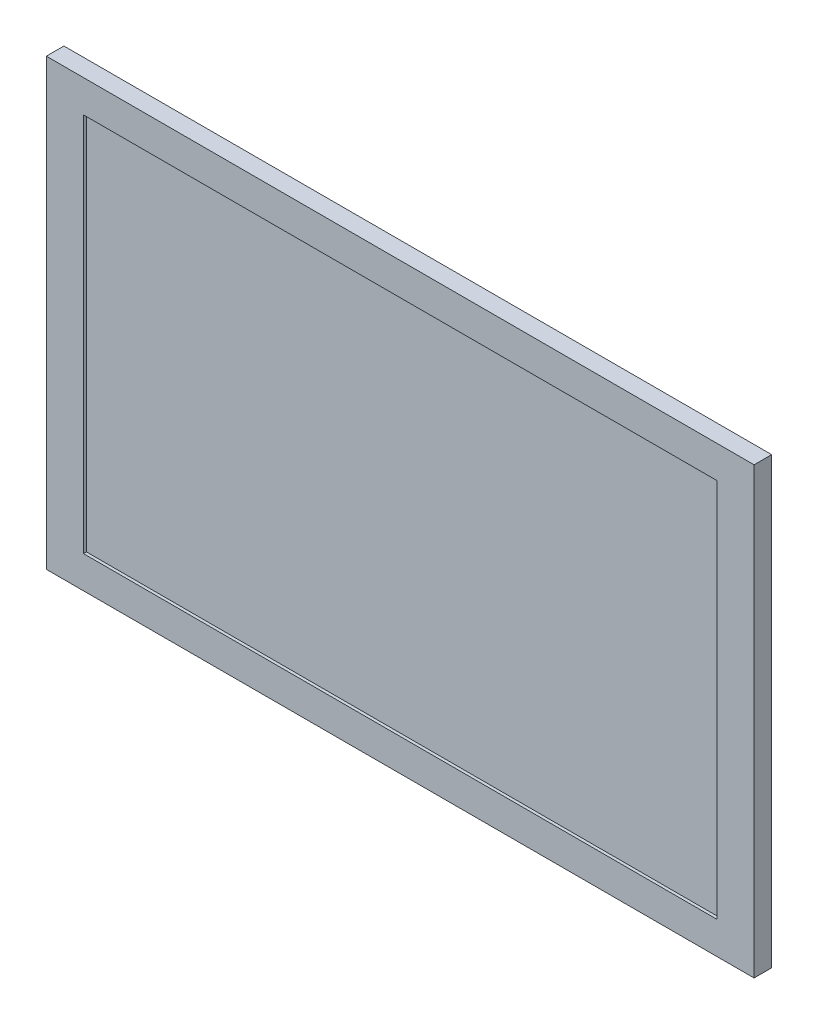
SolidWorks part; units mm, degrees
ref_plane "Front Plane" through (0, 0, 0) normal (0, 0, 1) x (1, 0, 0)
ref_plane "Top Plane" through (0, 0, 0) normal (0, 1, 0) x (1, 0, 0)
ref_plane "Right Plane" through (0, 0, 0) normal (1, 0, 0) x (0, 0, -1)
sketch "Sketch1" plane through (0, 0, 0) normal (0, 0, 1) x (1, 0, 0)
  line L1 (-60.35, 37.9) -> (60.35, 37.9)
  line L2 (-60.35, 37.9) -> (-60.35, -37.9)
  line L3 (-60.35, -37.9) -> (60.35, -37.9)
  line L4 (60.35, 37.9) -> (60.35, -37.9)
  line L5 (-60.35, 37.9) -> (60.35, -37.9) construction
  line L6 (-60.35, -37.9) -> (60.35, 37.9) construction
  point P0 (0, 0)
  dimension "D1" = 120.7
  dimension "D2" = 75.8
extrude "Boss-Extrude1" add sketch "Sketch1" along normal mid plane 3
sketch "Sketch2" plane through (0, 0, 1.5) normal (0, 0, 1) x (1, 0, 0)
  line L1 (-54, 32.4) -> (54, 32.4)
  line L2 (-54, 32.4) -> (-54, -32.4)
  line L3 (-54, -32.4) -> (54, -32.4)
  line L4 (54, 32.4) -> (54, -32.4)
  line L5 (-54, 32.4) -> (54, -32.4) construction
  line L6 (-54, -32.4) -> (54, 32.4) construction
  point P0 (0, 0)
  dimension "D1" = 108
  dimension "D2" = 64.8
extrude "Cut-Extrude1" cut sketch "Sketch2" against normal blind 0.5
